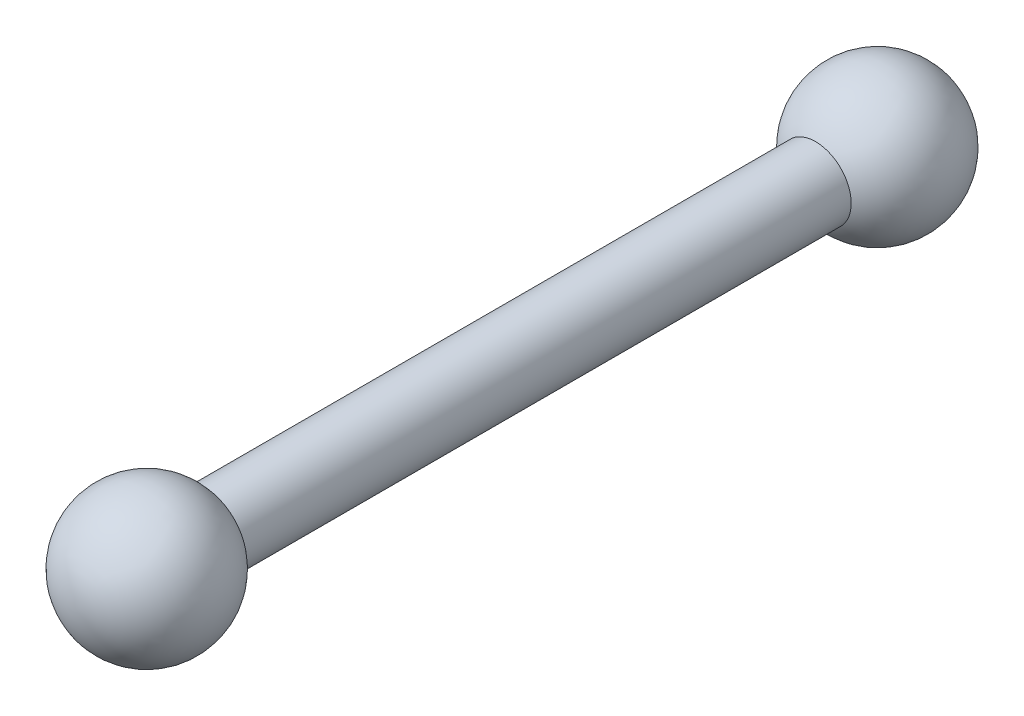
SolidWorks part; units mm, degrees
ref_plane "Front Plane" through (0, 0, 0) normal (0, 0, 1) x (1, 0, 0)
ref_plane "Top Plane" through (0, 0, 0) normal (0, 1, 0) x (1, 0, 0)
ref_plane "Right Plane" through (0, 0, 0) normal (1, 0, 0) x (0, 0, -1)
sketch "Sketch1" plane through (0, 0, 0) normal (0, 0, 1) x (1, 0, 0)
  circle A0 centre (0, 0) radius 2
  dimension "D1" = 4
extrude "Boss-Extrude1" add sketch "Sketch1" against normal blind 35
ref_plane "Plane1" through (0, 0, 3) normal (0, 0, 1) x (1, 0, 0)
sketch "Sketch2" plane through (0, 0, 3) normal (0, 0, 1) x (1, 0, 0)
  line L0 (0, 4) -> (0, -4) construction
  line L1 (0, 4) -> (0, -4)
  arc A1 (0, -4) -> (0, 4) centre (0, 0) ccw
  dimension "D1" = 8
revolve "Revolve1" add sketch "Sketch2" angle 360 about L0
ref_plane "Plane2" through (0, 0, -17.5) normal (0, 0, 1) x (1, 0, 0)
mirror "Mirror1" about plane through (0, 0, -17.5) normal (0, 0, 1) of "Revolve1"
